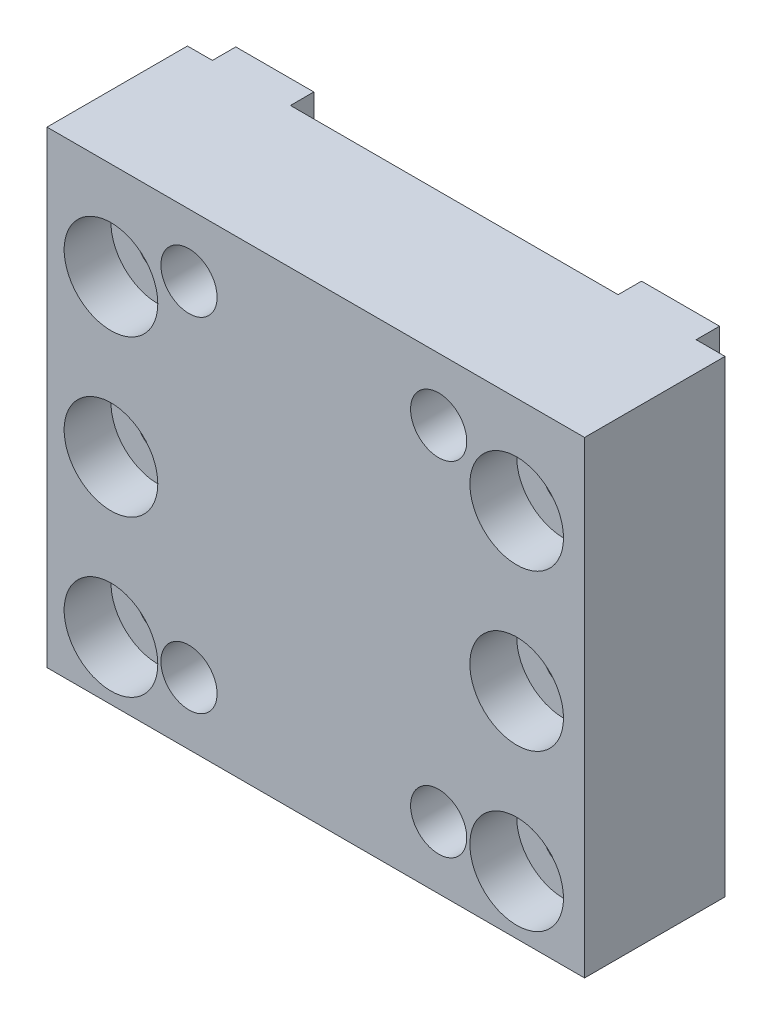
SolidWorks part; units mm, degrees
material "ABS"
ref_plane "前基準面" through (0, 0, 0) normal (0, 0, 1) x (1, 0, 0)
ref_plane "上基準面" through (0, 0, 0) normal (0, 1, 0) x (1, 0, 0)
ref_plane "右基準面" through (0, 0, 0) normal (1, 0, 0) x (0, 0, -1)
sketch "草圖1" plane through (0, 0, 0) normal (0, 0, 1) x (1, 0, 0)
  line L1 (0, 0) -> (70, 0)
  line L2 (0, 0) -> (0, 30)
  line L3 (0, 30) -> (70, 30)
  line L4 (70, 0) -> (70, 30)
  dimension "D1" = 70
  dimension "D2" = 30
extrude "填料-伸長1" add sketch "草圖1" along normal blind 9
sketch "草圖2" plane through (0, 0, 0) normal (-1, 0, 0) x (0, 0, 1)
  line L0 (9, 30) -> (9, 0) construction
  line L1 (9, 30) -> (-103.1, 30)
  line L2 (9, 30) -> (9, 0)
  line L3 (9, 0) -> (-103.1, 0)
  line L4 (-103.1, 30) -> (-103.1, 0)
  dimension "D1" = 30
  dimension "D2" = 112.1
extrude "填料-伸長2" add sketch "草圖2" along normal blind 8
sketch "草圖3" plane through (70, 0, 0) normal (1, 0, 0) x (0, 0, -1)
  line L5 (-9, 30) -> (33.6, 30)
  line L6 (-9, 30) -> (-9, 0)
  line L7 (-9, 0) -> (33.6, 0)
  line L8 (33.6, 30) -> (33.6, 0)
  dimension "D1" = 42.6
extrude "填料-伸長3" add sketch "草圖3" along normal blind 8
sketch "草圖5" plane through (0, 0, -33.6) normal (0, 0, -1) x (-1, 0, 0)
  line L5 (-78, 30) -> (-59.5, 30)
  line L6 (-78, 30) -> (-78, 0)
  line L11 (-78, 0) -> (-59.5, 0)
  line L12 (-59.5, 30) -> (-59.5, 0)
  circle A6 centre (-65.75, 26) radius 2
  circle A7 centre (-65.75, 18) radius 2
  circle A8 centre (-65.75, 10) radius 2
  dimension "D3" = 8
  dimension "D1" = 18.5
  dimension "D2" = 30
  dimension "D4" = 8
  dimension "D5" = 10
  dimension "D6" = 6.25
  dimension "D7" = 6.25
  dimension "D8" = 6.25
extrude "填料-伸長4" add sketch "草圖5" along normal blind 5.5
sketch "草圖11" plane through (-8, 0, 0) normal (-1, 0, 0) x (0, 0, 1)
  line L0 (9, 30) -> (-103.1, 30) construction
  line L2 (9, 0) -> (9, 30) construction
  circle A0 centre (-23, 23) radius 2
  circle A1 centre (-23, 15) radius 2
  circle A2 centre (-23, 7) radius 2
  circle A3 centre (-15, 23) radius 2
  circle A4 centre (-15, 15) radius 2
  circle A5 centre (-15, 7) radius 2
  circle A6 centre (-7, 23) radius 2
  circle A7 centre (-7, 15) radius 2
  circle A8 centre (-7, 7) radius 2
  dimension "D1" = 8
  dimension "D6" = 4
  dimension "D2" = 8
  dimension "D3" = 7
  dimension "D4" = 16
  dimension "D5" = 3
extrude "除料-伸長4" cut sketch "草圖11" against normal blind 8
sketch "草圖12" plane through (0, 0, -103.1) normal (0, 0, -1) x (-1, 0, 0)
  line L0 (8, 30) -> (0, 30) construction
  line L2 (0, 30) -> (0, 0) construction
  circle A0 centre (3, 23) radius 1.8
  circle A1 centre (3, 15) radius 1.8
  circle A2 centre (3, 7) radius 1.8
  dimension "D1" = 8
  dimension "D5" = 3.6
  dimension "D6" = 3.6
  dimension "D7" = 3.6
  dimension "D2" = 8
  dimension "D3" = 7
  dimension "D4" = 3
extrude "除料-伸長6" cut sketch "草圖12" against normal blind 8
sketch "草圖13" plane through (78, 0, 0) normal (1, 0, 0) x (0, 0, -1)
  line L0 (39.1, 30) -> (39.1, 0) construction
  circle A3 centre (9.1, 23) radius 2
  circle A4 centre (9.1, 15) radius 2
  circle A5 centre (9.1, 7) radius 2
  circle A6 centre (17.1, 23) radius 2
  circle A7 centre (17.1, 15) radius 2
  circle A8 centre (17.1, 7) radius 2
  circle A9 centre (25.1, 23) radius 2
  circle A10 centre (25.1, 15) radius 2
  circle A11 centre (25.1, 7) radius 2
  dimension "D1" = 8
  dimension "D2" = 8
  dimension "D3" = 8
  dimension "D4" = 8
  dimension "D6" = 8
  dimension "D5" = 8
  dimension "D7" = 14
  dimension "D8" = 8
  dimension "D9" = 8
extrude "除料-伸長7" cut sketch "草圖13" against normal blind 8
sketch "草圖14" plane through (-8, 0, 0) normal (-1, 0, 0) x (0, 0, 1)
  line L1 (9, 30) -> (-103.1, 30) construction
  line L2 (-103.1, 30) -> (-103.1, 0) construction
  circle A0 centre (-85.1, 23) radius 2
  circle A1 centre (-85.1, 15) radius 2
  circle A2 centre (-85.1, 7) radius 2
  circle A3 centre (-77.1, 23) radius 2
  circle A4 centre (-77.1, 15) radius 2
  circle A5 centre (-77.1, 7) radius 2
  circle A6 centre (-69.1, 23) radius 2
  circle A7 centre (-69.1, 15) radius 2
  circle A8 centre (-69.1, 7) radius 2
  circle A9 centre (-61.1, 23) radius 2
  circle A10 centre (-61.1, 15) radius 2
  circle A11 centre (-61.1, 7) radius 2
  dimension "D1" = 8
  dimension "D6" = 4
  dimension "D2" = 8
  dimension "D3" = 7
  dimension "D5" = 18
  dimension "D4" = 4
extrude "除料-伸長8" cut sketch "草圖14" against normal blind 10
sketch "草圖19" plane through (0, 30, 0) normal (0, 1, 0) x (1, 0, 0)
  line L3 (19.6, 0) -> (24.6, 0)
  line L8 (45.6, 0) -> (50.6, 0)
  line L10 (19.6, 0) -> (19.6, -9)
  line L11 (78, -9) -> (-8, -9) construction
  line L12 (19.6, -9) -> (24.6, -9)
  line L13 (24.6, -9) -> (24.6, 0)
  line L14 (45.6, 0) -> (45.6, -9)
  line L15 (45.6, -9) -> (50.6, -9)
  line L16 (50.6, -9) -> (50.6, 0)
  dimension "D1" = 5
  dimension "D2" = 5
  dimension "D3" = 21
  dimension "D4" = 9
  dimension "D5" = 9
extrude "填料-伸長6" add sketch "草圖19" against normal blind 36.25
sketch "草圖20" plane through (0, 0, 0) normal (0, 0, -1) x (-1, 0, 0)
  line L0 (-70, 30) -> (0, 30) construction
  line L13 (-50.6, 30) -> (-45.6, 30)
  line L18 (-50.6, 30) -> (-50.6, 36.25)
  line L19 (-50.6, 36.25) -> (-45.6, 36.25)
  line L20 (-45.6, 30) -> (-45.6, 36.25)
  line L22 (-24.6, 30) -> (-19.6, 30)
  line L23 (-24.6, 30) -> (-24.6, 36.25)
  line L24 (-24.6, 36.25) -> (-19.6, 36.25)
  line L25 (-19.6, 30) -> (-19.6, 36.25)
  dimension "D1" = 5
  dimension "D2" = 6.25
  dimension "D3" = 19.4
  dimension "D4" = 21
  dimension "D5" = 5
  dimension "D6" = 6.25
extrude "填料-伸長7" add sketch "草圖20" against normal blind 9
sketch "草圖21" plane through (0, 0, 0) normal (0, 0, -1) x (-1, 0, 0)
  line L0 (-50.6, -6.25) -> (-45.6, -6.25) construction
  line L1 (-24.6, -6.25) -> (-19.6, -6.25) construction
  circle A1 centre (-48.1, 23.75) radius 1.3
  circle A2 centre (-48.1, 13.75) radius 1.3
  circle A3 centre (-48.1, 3.75) radius 1.3
  circle A4 centre (-22.1, 23.75) radius 1.3
  circle A5 centre (-22.1, 13.75) radius 1.3
  circle A6 centre (-22.1, 3.75) radius 1.3
  dimension "D1" = 2.6
  dimension "D2" = 2.6
  dimension "D3" = 2.6
  dimension "D4" = 2.6
  dimension "D5" = 2.6
  dimension "D6" = 2.6
  dimension "D7" = 10
  dimension "D8" = 10
  dimension "D9" = 10
  dimension "D10" = 10
  dimension "D11" = 10
  dimension "D12" = 10
extrude "除料-伸長10" cut sketch "草圖21" against normal blind 9
sketch "草圖25" plane through (0, 36.25, 0) normal (0, 1, 0) x (1, 0, 0)
  line L1 (19.6, 0) -> (24.6, 0)
  line L2 (19.6, 0) -> (19.6, 1.5)
  line L3 (19.6, 1.5) -> (24.6, 1.5)
  line L4 (24.6, 0) -> (24.6, 1.5)
  line L5 (45.6, 0) -> (50.6, 0)
  line L6 (45.6, 0) -> (45.6, 1.5)
  line L7 (45.6, 1.5) -> (50.6, 1.5)
  line L8 (50.6, 0) -> (50.6, 1.5)
  dimension "D1" = 1.5
  dimension "D2" = 1.5
  dimension "D3" = 5
  dimension "D4" = 5
extrude "填料-伸長8" add sketch "草圖25" against normal blind 42.5
sketch "草圖26" plane through (0, 0, -1.5) normal (0, 0, -1) x (-1, 0, 0)
  line L0 (-50.6, -6.25) -> (-50.6, 36.25) construction
  line L4 (-50.6, -6.25) -> (-45.6, -6.25) construction
  line L5 (-24.6, -6.25) -> (-19.6, -6.25) construction
  line L6 (-24.6, -6.25) -> (-24.6, 36.25) construction
  circle A0 centre (-48.1, 23.75) radius 1.3
  circle A1 centre (-48.1, 13.75) radius 1.3
  circle A2 centre (-48.1, 3.75) radius 1.3
  circle A3 centre (-22.1, 23.75) radius 1.3
  circle A4 centre (-22.1, 13.75) radius 1.3
  circle A5 centre (-22.1, 3.75) radius 1.3
  dimension "D1" = 2.6
  dimension "D2" = 2.6
  dimension "D3" = 2.6
  dimension "D4" = 2.6
  dimension "D5" = 2.6
  dimension "D6" = 2.6
  dimension "D7" = 2.5
  dimension "D8" = 10
  dimension "D9" = 10
  dimension "D10" = 10
  dimension "D11" = 10
  dimension "D12" = 10
  dimension "D13" = 10
  dimension "D14" = 2.5
extrude "除料-伸長14" cut sketch "草圖26" against normal blind 1.5
sketch "草圖27" plane through (0, 0, 9) normal (0, 0, 1) x (1, 0, 0)
  line L1 (19.6, 36.25) -> (24.6, 36.25)
  line L2 (19.6, 36.25) -> (19.6, 30)
  line L3 (19.6, 30) -> (24.6, 30)
  line L4 (24.6, 36.25) -> (24.6, 30)
  line L5 (45.6, 36.25) -> (50.6, 36.25)
  line L6 (45.6, 36.25) -> (45.6, 30)
  line L7 (45.6, 30) -> (50.6, 30)
  line L8 (50.6, 36.25) -> (50.6, 30)
  line L9 (19.6, 0) -> (24.6, 0)
  line L10 (19.6, 0) -> (19.6, -6.25)
  line L11 (19.6, -6.25) -> (24.6, -6.25)
  line L12 (24.6, 0) -> (24.6, -6.25)
  line L13 (45.6, 0) -> (50.6, 0)
  line L14 (45.6, 0) -> (45.6, -6.25)
  line L15 (45.6, -6.25) -> (50.6, -6.25)
  line L16 (50.6, 0) -> (50.6, -6.25)
extrude "除料-伸長15" cut sketch "草圖27" against normal blind 11
sketch "草圖28" plane through (0, 0, 9) normal (0, 0, 1) x (1, 0, 0)
  circle A0 centre (22.1, 23.75) radius 3
  circle A1 centre (22.1, 13.75) radius 3
  circle A2 centre (22.1, 3.75) radius 3
  circle A3 centre (48.1, 13.75) radius 3
  circle A4 centre (48.1, 3.75) radius 3
  circle A5 centre (48.1, 23.75) radius 3
  dimension "D1" = 6
  dimension "D2" = 6
  dimension "D3" = 6
  dimension "D4" = 6
  dimension "D5" = 6
  dimension "D6" = 6
extrude "除料-伸長16" cut sketch "草圖28" against normal blind 3
sketch "草圖29" plane through (0, 30, 0) normal (0, 1, 0) x (1, 0, 0)
  line L0 (59.5, 39.1) -> (59.5, 33.6) construction
  line L1 (0, 0) -> (-8, 0)
  line L2 (0, 0) -> (0, 103.1)
  line L3 (0, 103.1) -> (-8, 103.1)
  line L4 (-8, 0) -> (-8, 103.1)
  line L5 (70, 0) -> (78, 0)
  line L6 (70, 0) -> (70, 39.1)
  line L7 (70, 39.1) -> (78, 39.1)
  line L8 (78, 0) -> (78, 39.1)
  line L9 (70, 39.1) -> (59.5, 39.1)
  line L10 (70, 39.1) -> (70, 33.6)
  line L11 (70, 33.6) -> (59.5, 33.6)
  line L12 (59.5, 39.1) -> (59.5, 33.6)
  line M1 (-8, 103.1) -> (-8, -9)
  line M3 (78, -9) -> (78, 39.1)
  line M4 (78, 39.1) -> (59.5, 39.1)
  line M5 (59.5, 39.1) -> (59.5, 33.6)
  line M6 (59.5, 33.6) -> (70, 33.6)
  line M7 (70, 33.6) -> (70, 0)
  line M17 (0, 0) -> (0, 103.1)
  line M18 (0, 103.1) -> (-8, 103.1)
extrude "除料-伸長17" cut sketch "草圖29" against normal blind 30 contours L1 M17 M18 M1 | L6 M6 M4 M5 | L6 L5 M7 M3 M4
sketch "草圖30" plane through (0, 0, 9) normal (0, 0, 1) x (1, 0, 0)
  line L0 (78, 30) -> (-8, 30) construction
  line L1 (-8, 0) -> (-8, 30) construction
  circle A0 centre (-4, 23) radius 1.8
  circle A1 centre (-4, 15) radius 1.8
  circle A2 centre (-4, 7) radius 1.8
  dimension "D1" = 8
  dimension "D3" = 3.6
  dimension "D2" = 8
  dimension "D4" = 7
  dimension "D5" = 4
extrude "除料-伸長18" cut sketch "草圖30" against normal blind 10
sketch "草圖31" plane through (0, 0, 9) normal (0, 0, 1) x (1, 0, 0)
  circle A0 centre (-4, 15) radius 3.6
  circle A1 centre (-4, 7) radius 3.6
  circle A2 centre (-4, 23) radius 3.6
  dimension "D1" = 7.2
extrude "除料-伸長19" cut sketch "草圖31" against normal blind 3
sketch "草圖32" plane through (0, 0, 9) normal (0, 0, 1) x (1, 0, 0)
  line L0 (-8, 0) -> (78, 0) construction
  line L1 (78, 30) -> (78, 0) construction
  circle A0 centre (65.2, 23) radius 1.8
  circle A1 centre (65.2, 15) radius 1.8
  circle A2 centre (65.2, 7) radius 1.8
  dimension "D5" = 3.6
  dimension "D1" = 8
  dimension "D2" = 8
  dimension "D3" = 7
  dimension "D4" = 12.8
extrude "除料-伸長20" cut sketch "草圖32" against normal blind 10
sketch "草圖33" plane through (0, 0, 9) normal (0, 0, 1) x (1, 0, 0)
  circle A0 centre (65.2, 23) radius 3.6
  circle A1 centre (65.2, 15) radius 3.6
  circle A2 centre (65.2, 7) radius 3.6
  dimension "D1" = 7.2
extrude "除料-伸長21" cut sketch "草圖33" against normal blind 3
sketch "草圖35" plane through (0, 0, 0) normal (0, 0, -1) x (-1, 0, 0)
  line L0 (-45.6, 0) -> (-45.6, 30) construction
  line L1 (-24.6, 0) -> (-45.6, 0) construction
  circle A0 centre (-43.1, 4) radius 1.8
  circle A1 centre (-43.1, 26) radius 1.8
  circle A2 centre (-27.1, 26) radius 1.8
  circle A3 centre (-27.1, 4) radius 1.8
  dimension "D1" = 3.6
  dimension "D2" = 2.5
  dimension "D3" = 4
  dimension "D4" = 2
  dimension "D5" = 2
extrude "除料-伸長22" cut sketch "草圖35" against normal up to next
sketch "草圖36" plane through (0, 0, 9) normal (0, 0, 1) x (1, 0, 0)
  line L0 (-8, 0) -> (78, 0) construction
  line L1 (78, 30) -> (70.45, 30)
  line L2 (78, 30) -> (78, 0)
  line L3 (78, 0) -> (70.45, 0)
  line L4 (70.45, 30) -> (70.45, 0)
  dimension "D1" = 7.55
extrude "除料-伸長23" cut sketch "草圖36" against normal blind 10
sketch "草圖37" plane through (0, 0, 9) normal (0, 0, 1) x (1, 0, 0)
  line L0 (-8, 0) -> (70.45, 0) construction
  line L1 (70.45, 30) -> (52.45, 30)
  line L2 (70.45, 30) -> (70.45, 0)
  line L3 (70.45, 0) -> (52.45, 0)
  line L4 (52.45, 30) -> (52.45, 0)
  line L6 (-8, 30) -> (18, 30)
  line L7 (-8, 30) -> (-8, 0)
  line L8 (-8, 0) -> (18, 0)
  line L9 (18, 30) -> (18, 0)
  dimension "D1" = 26
  dimension "D2" = 18
extrude "除料-伸長24" cut sketch "草圖37" against normal blind 10
